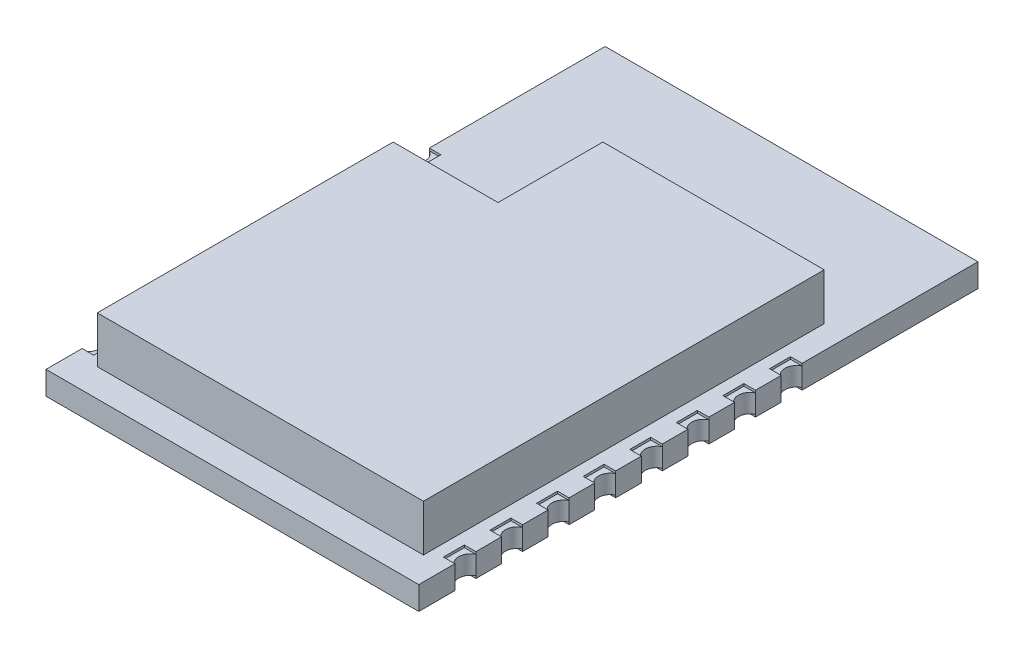
SolidWorks part; units mm, degrees
ref_plane "前基準面" through (0, 0, 0) normal (0, 0, 1) x (1, 0, 0)
ref_plane "上基準面" through (0, 0, 0) normal (0, 1, 0) x (1, 0, 0)
ref_plane "右基準面" through (0, 0, 0) normal (1, 0, 0) x (0, 0, -1)
sketch "草圖1" plane through (0, 0, 0) normal (0, 1, 0) x (1, 0, 0)
  line L5 (-8, 12) -> (8, 12)
  line L6 (-8, 12) -> (-8, -12)
  line L7 (-8, -12) -> (8, -12)
  line L8 (8, 12) -> (8, -12)
  line L9 (-8, 12) -> (8, -12) construction
  line L10 (-8, -12) -> (8, 12) construction
  point P0 (0, 0)
  dimension "D1" = 16
  dimension "24" = 24
extrude "填料-伸長1" add sketch "草圖1" along normal blind 1
sketch "草圖2" plane through (0, 1, 0) normal (0, 1, 0) x (1, 0, 0)
  line L0 (0, 0) -> (0, -5.3119)
  line L1 (-8.003, -9.55) -> (-7.503, -9.55)
  line L2 (-8.003, -9.55) -> (-8.003, -10.45)
  line L3 (-8.003, -10.45) -> (-7.503, -10.45)
  line L4 (-7.503, -9.55) -> (-7.503, -10.45)
  line L5 (8.003, -10.45) -> (7.503, -10.45)
  line L6 (7.503, -9.55) -> (7.503, -10.45)
  line L7 (8.003, -9.55) -> (7.503, -9.55)
  line L8 (8.003, -9.55) -> (8.003, -10.45)
  line L9 (-8.003, -7.55) -> (-8.003, -8.45)
  line L10 (-8.003, -7.55) -> (-7.503, -7.55)
  line L11 (-7.503, -7.55) -> (-7.503, -8.45)
  line L12 (-8.003, -8.45) -> (-7.503, -8.45)
  line L13 (-8.003, -5.55) -> (-8.003, -6.45)
  line L14 (-8.003, -5.55) -> (-7.503, -5.55)
  line L15 (-7.503, -5.55) -> (-7.503, -6.45)
  line L16 (-8.003, -6.45) -> (-7.503, -6.45)
  line L17 (-8.003, -3.55) -> (-8.003, -4.45)
  line L18 (-8.003, -3.55) -> (-7.503, -3.55)
  line L19 (-7.503, -3.55) -> (-7.503, -4.45)
  line L20 (-8.003, -4.45) -> (-7.503, -4.45)
  line L21 (-8.003, -1.55) -> (-8.003, -2.45)
  line L22 (-8.003, -1.55) -> (-7.503, -1.55)
  line L23 (-7.503, -1.55) -> (-7.503, -2.45)
  line L24 (-8.003, -2.45) -> (-7.503, -2.45)
  line L25 (-8.003, 0.45) -> (-8.003, -0.45)
  line L26 (-8.003, 0.45) -> (-7.503, 0.45)
  line L27 (-7.503, 0.45) -> (-7.503, -0.45)
  line L28 (-8.003, -0.45) -> (-7.503, -0.45)
  line L29 (-8.003, 2.45) -> (-8.003, 1.55)
  line L30 (-8.003, 2.45) -> (-7.503, 2.45)
  line L31 (-7.503, 2.45) -> (-7.503, 1.55)
  line L32 (-8.003, 1.55) -> (-7.503, 1.55)
  line L33 (-8.003, 4.45) -> (-8.003, 3.55)
  line L34 (-8.003, 4.45) -> (-7.503, 4.45)
  line L35 (-7.503, 4.45) -> (-7.503, 3.55)
  line L36 (-8.003, 3.55) -> (-7.503, 3.55)
  line L42 (8.003, -8.45) -> (7.503, -8.45)
  line L43 (7.503, -7.55) -> (7.503, -8.45)
  line L44 (8.003, -7.55) -> (7.503, -7.55)
  line L45 (8.003, -7.55) -> (8.003, -8.45)
  line L46 (8.003, -6.45) -> (7.503, -6.45)
  line L47 (7.503, -5.55) -> (7.503, -6.45)
  line L48 (8.003, -5.55) -> (7.503, -5.55)
  line L49 (8.003, -5.55) -> (8.003, -6.45)
  line L50 (8.003, -4.45) -> (7.503, -4.45)
  line L51 (7.503, -3.55) -> (7.503, -4.45)
  line L52 (8.003, -3.55) -> (7.503, -3.55)
  line L53 (8.003, -3.55) -> (8.003, -4.45)
  line L54 (8.003, -2.45) -> (7.503, -2.45)
  line L55 (7.503, -1.55) -> (7.503, -2.45)
  line L56 (8.003, -1.55) -> (7.503, -1.55)
  line L57 (8.003, -1.55) -> (8.003, -2.45)
  line L58 (8.003, -0.45) -> (7.503, -0.45)
  line L59 (7.503, 0.45) -> (7.503, -0.45)
  line L60 (8.003, 0.45) -> (7.503, 0.45)
  line L61 (8.003, 0.45) -> (8.003, -0.45)
  line L62 (8.003, 1.55) -> (7.503, 1.55)
  line L63 (7.503, 2.45) -> (7.503, 1.55)
  line L64 (8.003, 2.45) -> (7.503, 2.45)
  line L65 (8.003, 2.45) -> (8.003, 1.55)
  line L66 (8.003, 3.55) -> (7.503, 3.55)
  line L67 (7.503, 4.45) -> (7.503, 3.55)
  line L68 (8.003, 4.45) -> (7.503, 4.45)
  line L69 (8.003, 4.45) -> (8.003, 3.55)
  point P4 (-8.003, -10)
  line M6 (8, -12) -> (8, 12)
  line M8 (-8, 12) -> (-8, -12)
  dimension "D1" = 2
  dimension "D2" = 8
  dimension "D3" = 8
extrude "除料-伸長1" cut sketch "草圖2" against normal blind 0.1 contours L32 L31 L30 M8 | L28 L27 L26 M8 | L24 L23 L22 M8 | L20 L19 L18 M8 | L16 L15 L14 M8 | L12 L11 L10 M8 | L4 L1 L3 M8 | L7 L6 L5 M6 | L44 L43 L42 M6 | L48 L47 L46 M6 | L52 L51 L50 M6 | L56 L55 L54 M6 | L60 L59 L58 M6 | L68 L67 L66 M6 | L64 L63 L62 M6 | L35 L36 L33 L34
sketch "草圖3" plane through (0, 0, 0) normal (0, -1, 0) x (1, 0, 0)
  line L0 (7, 7.55) -> (7, 8.45)
  line L1 (8, 12) -> (8, -12) construction
  line L6 (7, 9.55) -> (8, 9.55)
  line L7 (7, 9.55) -> (7, 10.45)
  line L8 (7, 10.45) -> (8, 10.45)
  line L9 (8, 9.55) -> (8, 10.45)
  line L10 (-8, 12) -> (8, 12) construction
  line L11 (7, 7.55) -> (8, 7.55)
  line L12 (8, 7.55) -> (8, 8.45)
  line L13 (7, 8.45) -> (8, 8.45)
  line L14 (7, 5.55) -> (7, 6.45)
  line L15 (7, 5.55) -> (8, 5.55)
  line L16 (8, 5.55) -> (8, 6.45)
  line L17 (7, 6.45) -> (8, 6.45)
  line L18 (7, 3.55) -> (7, 4.45)
  line L19 (7, 3.55) -> (8, 3.55)
  line L20 (8, 3.55) -> (8, 4.45)
  line L21 (7, 4.45) -> (8, 4.45)
  line L22 (7, 1.55) -> (7, 2.45)
  line L23 (7, 1.55) -> (8, 1.55)
  line L24 (8, 1.55) -> (8, 2.45)
  line L25 (7, 2.45) -> (8, 2.45)
  line L26 (7, -0.45) -> (7, 0.45)
  line L27 (7, -0.45) -> (8, -0.45)
  line L28 (8, -0.45) -> (8, 0.45)
  line L29 (7, 0.45) -> (8, 0.45)
  line L30 (7, -2.45) -> (7, -1.55)
  line L31 (7, -2.45) -> (8, -2.45)
  line L32 (8, -2.45) -> (8, -1.55)
  line L33 (7, -1.55) -> (8, -1.55)
  line L34 (7, -4.45) -> (7, -3.55)
  line L35 (7, -4.45) -> (8, -4.45)
  line L36 (8, -4.45) -> (8, -3.55)
  line L37 (7, -3.55) -> (8, -3.55)
  line L38 (0, 0) -> (0, -2.1829)
  line L39 (-7, 10.45) -> (-8, 10.45)
  line L40 (-8, 9.55) -> (-8, 10.45)
  line L41 (-7, 9.55) -> (-8, 9.55)
  line L42 (-7, 9.55) -> (-7, 10.45)
  line L43 (-7, -4.45) -> (-8, -4.45)
  line L44 (-8, -4.45) -> (-8, -3.55)
  line L45 (-7, -3.55) -> (-8, -3.55)
  line L46 (-7, -4.45) -> (-7, -3.55)
  line L47 (-7, -2.45) -> (-8, -2.45)
  line L48 (-8, -2.45) -> (-8, -1.55)
  line L49 (-7, -1.55) -> (-8, -1.55)
  line L50 (-7, -2.45) -> (-7, -1.55)
  line L51 (-7, -0.45) -> (-8, -0.45)
  line L52 (-8, -0.45) -> (-8, 0.45)
  line L53 (-7, 0.45) -> (-8, 0.45)
  line L54 (-7, -0.45) -> (-7, 0.45)
  line L55 (-7, 1.55) -> (-8, 1.55)
  line L56 (-8, 1.55) -> (-8, 2.45)
  line L57 (-7, 2.45) -> (-8, 2.45)
  line L58 (-7, 1.55) -> (-7, 2.45)
  line L59 (-7, 3.55) -> (-8, 3.55)
  line L60 (-8, 3.55) -> (-8, 4.45)
  line L61 (-7, 4.45) -> (-8, 4.45)
  line L62 (-7, 3.55) -> (-7, 4.45)
  line L63 (-7, 5.55) -> (-8, 5.55)
  line L64 (-8, 5.55) -> (-8, 6.45)
  line L65 (-7, 6.45) -> (-8, 6.45)
  line L66 (-7, 5.55) -> (-7, 6.45)
  line L67 (-7, 7.55) -> (-8, 7.55)
  line L68 (-8, 7.55) -> (-8, 8.45)
  line L69 (-7, 8.45) -> (-8, 8.45)
  line L70 (-7, 7.55) -> (-7, 8.45)
  point P8 (8, 10)
  point P72 (0, 0)
  dimension "D1" = 2
  dimension "D2" = 0.9
  dimension "D3" = 8
extrude "除料-伸長2" cut sketch "草圖3" against normal blind 0.1 contours L67 L70 L69 L9 | L63 L66 L65 L9 | L59 L62 L61 L9 | L51 L54 L53 L9 | L47 L50 L49 L9 | L43 L46 L45 L9 | L33 L30 L31 L7 | L29 L26 L27 L7 | L25 L22 L23 L7 | L21 L18 L19 L7 | L13 L0 L11 L7 | L8 L7 L6 | L41 L40 L39 L42 | L58 L57 L56 L55 | L36 L37 L34 L35 | L17 L16 L15 L14
sketch "草圖8" plane through (0, 1, 0) normal (0, 1, 0) x (1, 0, 0)
  line L0 (-8, -12) -> (8, -12) construction
  line L1 (-1, 0.6) -> (3.7, 0.6)
  line L2 (-1, 0.6) -> (-1, -4.1)
  line L3 (-1, -4.1) -> (3.7, -4.1)
  line L4 (3.7, 0.6) -> (3.7, -4.1)
  line L5 (-1, 0.6) -> (3.7, -4.1) construction
  line L6 (-1, -4.1) -> (3.7, 0.6) construction
  line L7 (-8, -2.45) -> (-8, -3.55) construction
  point P0 (1.35, -1.75)
  point P9 (0, 0)
  dimension "D1" = 7.9
  dimension "D2" = 7
  dimension "D3" = 4.7
  dimension "D4" = 4.7
extrude "除料-伸長3" cut sketch "草圖8" against normal blind 0.1
sketch "草圖12" plane through (0, 0.9, 0) normal (0, 1, 0) x (1, 0, 0)
  line L0 (-1, 0.6) -> (-1, -4.1) construction
  line L1 (-1, -4.1) -> (3.7, -4.1) construction
  circle A1 centre (-0.51, -3.65) radius 0.2
  circle A2 centre (0.42, -3.65) radius 0.2
  circle A3 centre (1.35, -3.65) radius 0.2
  circle A4 centre (2.28, -3.65) radius 0.2
  circle A5 centre (3.21, -3.65) radius 0.2
  circle A6 centre (-0.51, -2.72) radius 0.2
  circle A7 centre (0.42, -2.72) radius 0.2
  circle A8 centre (1.35, -2.72) radius 0.2
  circle A9 centre (2.28, -2.72) radius 0.2
  circle A10 centre (3.21, -2.72) radius 0.2
  circle A11 centre (-0.51, -1.79) radius 0.2
  circle A12 centre (0.42, -1.79) radius 0.2
  circle A13 centre (1.35, -1.79) radius 0.2
  circle A14 centre (2.28, -1.79) radius 0.2
  circle A15 centre (3.21, -1.79) radius 0.2
  circle A16 centre (-0.51, -0.86) radius 0.2
  circle A17 centre (0.42, -0.86) radius 0.2
  circle A18 centre (1.35, -0.86) radius 0.2
  circle A19 centre (2.28, -0.86) radius 0.2
  circle A20 centre (3.21, -0.86) radius 0.2
  circle A21 centre (-0.51, 0.07) radius 0.2
  circle A22 centre (0.42, 0.07) radius 0.2
  circle A23 centre (1.35, 0.07) radius 0.2
  circle A24 centre (2.28, 0.07) radius 0.2
  circle A25 centre (3.21, 0.07) radius 0.2
  dimension "D1" = 0.49
  dimension "D2" = 0.45
  dimension "D3" = 5
  dimension "D4" = 5
extrude "除料-伸長4" cut sketch "草圖12" against normal blind 0.1
sketch "草圖13" plane through (0, 1, 0) normal (0, 1, 0) x (1, 0, 0)
  line L5 (-1, 0.6) -> (3.7, 0.6)
  line L6 (-1, 0.6) -> (-1, -4.1)
  line L7 (-1, -4.1) -> (3.7, -4.1)
  line L8 (3.7, 0.6) -> (3.7, -4.1)
extrude "填料-伸長2" add sketch "草圖13" against normal blind 0.5
sketch "草圖15" plane through (0, 0, 0) normal (0, -1, 0) x (1, 0, 0)
  line L0 (-8, 12) -> (8, 12) construction
  line L1 (1, -0.6) -> (-3.7, -0.6)
  line L2 (1, -0.6) -> (1, 4.1)
  line L3 (1, 4.1) -> (-3.7, 4.1)
  line L4 (-3.7, -0.6) -> (-3.7, 4.1)
  line L5 (1, -0.6) -> (-3.7, 4.1) construction
  line L6 (1, 4.1) -> (-3.7, -0.6) construction
  line L7 (8, 1.55) -> (8, 0.45) construction
  point P0 (-1.35, 1.75)
  point P9 (8, 1)
  dimension "D1" = 7.9
  dimension "D2" = 7
  dimension "D3" = 4.7
  dimension "D4" = 4.7
extrude "除料-伸長5" cut sketch "草圖15" against normal blind 0.1
sketch "草圖16" plane through (0, 0, 0) normal (0, -1, 0) x (1, 0, 0)
  line L0 (1, 4.1) -> (-3.7, 4.1) construction
  line L1 (1, -0.6) -> (1, 4.1) construction
  circle A0 centre (0.51, 3.61) radius 0.2
  circle A1 centre (-0.42, 3.61) radius 0.2
  circle A2 centre (-1.35, 3.61) radius 0.2
  circle A3 centre (-2.28, 3.61) radius 0.2
  circle A4 centre (-3.21, 3.61) radius 0.2
  circle A5 centre (-3.21, 2.68) radius 0.2
  circle A6 centre (-2.28, 2.68) radius 0.2
  circle A7 centre (-1.35, 2.68) radius 0.2
  circle A8 centre (-0.42, 2.68) radius 0.2
  circle A9 centre (0.51, 2.68) radius 0.2
  circle A10 centre (-3.21, 1.75) radius 0.2
  circle A11 centre (-2.28, 1.75) radius 0.2
  circle A12 centre (-1.35, 1.75) radius 0.2
  circle A13 centre (-0.42, 1.75) radius 0.2
  circle A14 centre (0.51, 1.75) radius 0.2
  circle A15 centre (-3.21, 0.82) radius 0.2
  circle A16 centre (-2.28, 0.82) radius 0.2
  circle A17 centre (-1.35, 0.82) radius 0.2
  circle A18 centre (-0.42, 0.82) radius 0.2
  circle A19 centre (0.51, 0.82) radius 0.2
  circle A20 centre (-3.21, -0.11) radius 0.2
  circle A21 centre (-2.28, -0.11) radius 0.2
  circle A22 centre (-1.35, -0.11) radius 0.2
  circle A23 centre (-0.42, -0.11) radius 0.2
  circle A24 centre (0.51, -0.11) radius 0.2
  dimension "D1" = 0.49
  dimension "D2" = 0.49
  dimension "D3" = 5
  dimension "D4" = 5
extrude "除料-伸長6" cut sketch "草圖16" against normal blind 0.25
sketch "草圖17" plane through (0, 1, 0) normal (0, 1, 0) x (1, 0, 0)
  line L0 (-8, -12) -> (8, -12) construction
  line L5 (-2.5, 6.4) -> (7, 6.4)
  line L6 (-7, 1.4) -> (-7, -10.8)
  line L7 (-7, -10.8) -> (7, -10.8)
  line L8 (7, 6.4) -> (7, -10.8)
  line L9 (-8, 12) -> (-8, 4.45) construction
  line L10 (8, 4.45) -> (8, 12) construction
  line L16 (-2.5, 6.4) -> (-2.5, 1.9)
  line L17 (-2.5, 1.9) -> (-7, 1.9)
  line L18 (-7, 1.9) -> (-7, 1.4)
  dimension "D1" = 1.2
  dimension "D2" = 1
  dimension "D3" = 1
extrude "填料-伸長4" add sketch "草圖17" along normal blind 2
sketch "草圖18" plane through (0, 1, 0) normal (0, 1, 0) x (1, 0, 0)
  line L1 (-8, 4.45) -> (-8, 3.55)
  line L3 (-8, 2.45) -> (-8, 1.55)
  line L4 (-8, 0.45) -> (-8, -0.45)
  line L5 (-8, -1.55) -> (-8, -2.45)
  line L6 (-8, -3.55) -> (-8, -4.45)
  line L7 (-8, -5.55) -> (-8, -6.45)
  line L8 (-8, -7.55) -> (-8, -8.45)
  line L9 (-8, -9.55) -> (-8, -10.45)
  line L12 (8, 4.45) -> (8, 3.55)
  line L13 (8, 2.45) -> (8, 1.55)
  line L14 (8, 0.45) -> (8, -0.45)
  line L15 (8, -1.55) -> (8, -2.45)
  line L16 (8, -3.55) -> (8, -4.45)
  line L17 (8, -5.55) -> (8, -6.45)
  line L18 (8, -7.55) -> (8, -8.45)
  line L19 (8, -9.55) -> (8, -10.45)
  arc A0 (-8, 4.45) -> (-8, 3.55) centre (-8.2179, 4) cw
  arc A1 (-8, 2.45) -> (-8, 1.55) centre (-8.2179, 2) cw
  arc A2 (-8, 0.45) -> (-8, -0.45) centre (-8.2179, 0) cw
  arc A3 (-8, -1.55) -> (-8, -2.45) centre (-8.2179, -2) cw
  arc A4 (-8, -3.55) -> (-8, -4.45) centre (-8.2179, -4) cw
  arc A5 (-8, -5.55) -> (-8, -6.45) centre (-8.2179, -6) cw
  arc A6 (-8, -7.55) -> (-8, -8.45) centre (-8.2179, -8) cw
  arc A7 (-8, -9.55) -> (-8, -10.45) centre (-8.2179, -10) cw
  arc A8 (8, 4.45) -> (8, 3.55) centre (8.2179, 4) ccw
  arc A9 (8, 2.45) -> (8, 1.55) centre (8.2179, 2) ccw
  arc A10 (8, 0.45) -> (8, -0.45) centre (8.2179, 0) ccw
  arc A11 (8, -1.55) -> (8, -2.45) centre (8.2179, -2) ccw
  arc A12 (8, -3.55) -> (8, -4.45) centre (8.2179, -4) ccw
  arc A13 (8, -5.55) -> (8, -6.45) centre (8.2179, -6) ccw
  arc A14 (8, -7.55) -> (8, -8.45) centre (8.2179, -8) ccw
  arc A15 (8, -9.55) -> (8, -10.45) centre (8.2179, -10) ccw
  dimension "D1" = 8
extrude "除料-伸長7" cut sketch "草圖18" against normal blind 2
